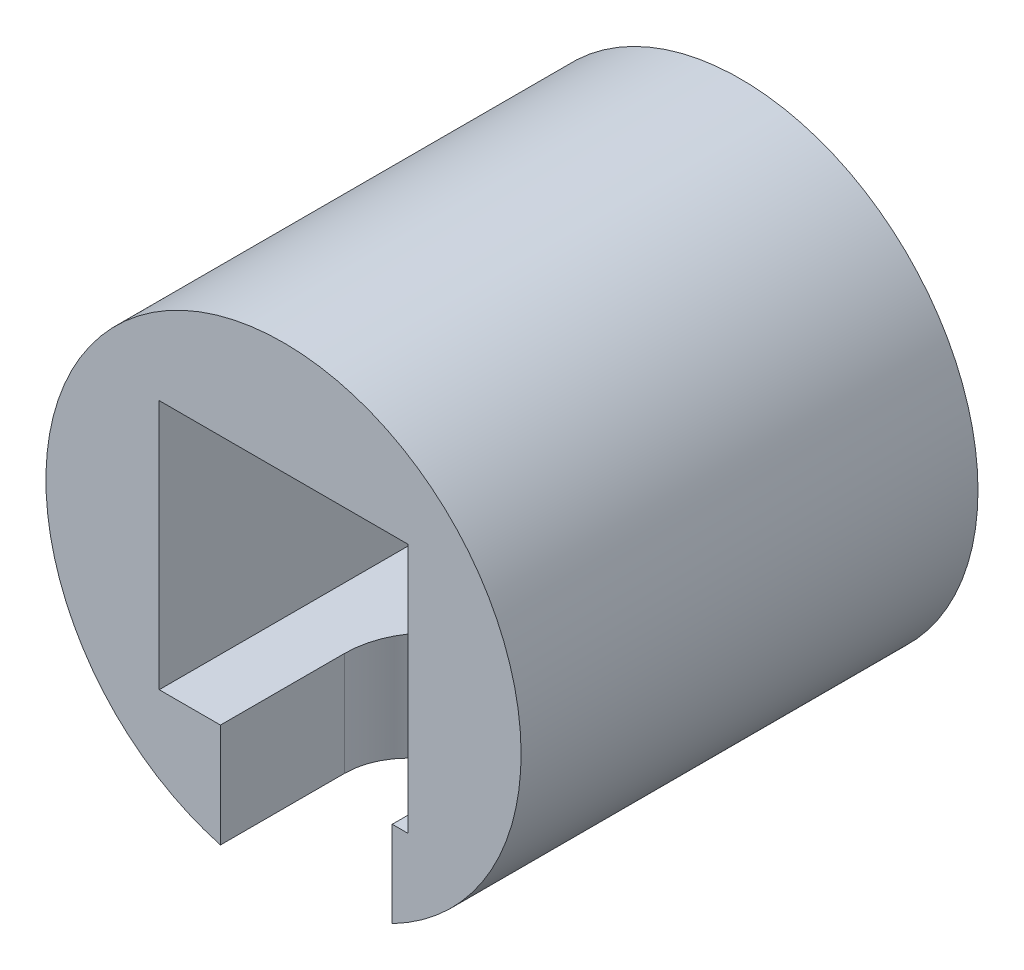
SolidWorks part; units mm, degrees
ref_plane "Front Plane" through (0, 0, 0) normal (0, 0, 1) x (1, 0, 0)
ref_plane "Top Plane" through (0, 0, 0) normal (0, 1, 0) x (1, 0, 0)
ref_plane "Right Plane" through (0, 0, 0) normal (1, 0, 0) x (0, 0, -1)
sketch "Sketch1" plane through (0, 0, 0) normal (0, 0, 1) x (1, 0, 0)
  circle A0 centre (0, 0) radius 3
  circle A1 centre (0, 0) radius 13
extrude "Boss-Extrude1" add sketch "Sketch1" along normal blind 25
sketch "Sketch2" plane through (0, 0, 0) normal (0, 1, 0) x (1, 0, 0)
  line L5 (-6.8, -25) -> (6.8, -25)
  line L6 (-6.8, -25) -> (-6.8, -8.1199)
  line L8 (6.8, -25) -> (6.8, -6.5549)
  arc A2 (6.8, -6.5549) -> (-6.8, -8.1199) centre (1.25, -18.2) ccw
extrude "Cut-Extrude1" cut sketch "Sketch2" against normal mid plane 13.7
sketch "Sketch3" plane through (0, 0, 0) normal (0, 1, 0) x (1, 0, 0)
  line L5 (-3.45, -18.2) -> (-3.45, -25)
  line L6 (-3.45, -25) -> (5.95, -25)
  line L7 (5.95, -18.2) -> (5.95, -25)
  arc A1 (5.95, -18.2) -> (-3.45, -18.2) centre (1.25, -18.2) ccw
extrude "Cut-Extrude2" cut sketch "Sketch3" against normal up to surface (11.5584 mm away)
